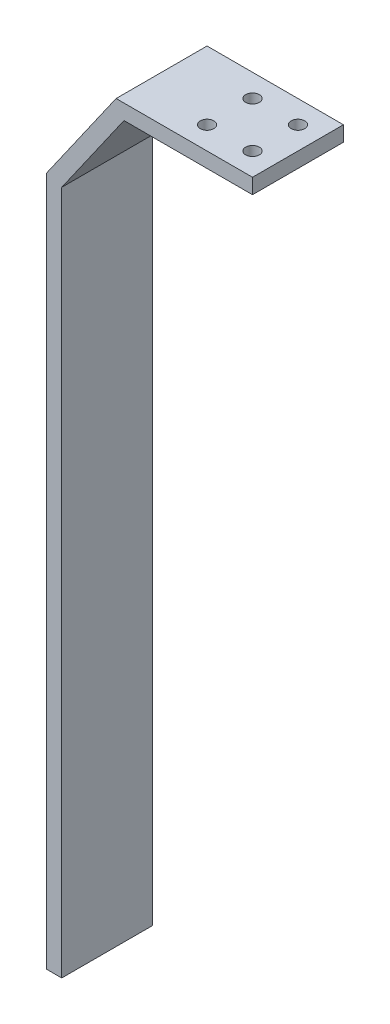
SolidWorks part; units mm, degrees
ref_plane "Front Plane" through (0, 0, 0) normal (0, 0, 1) x (1, 0, 0)
ref_plane "Top Plane" through (0, 0, 0) normal (0, 1, 0) x (1, 0, 0)
ref_plane "Right Plane" through (0, 0, 0) normal (1, 0, 0) x (0, 0, -1)
sketch "Sketch1" plane through (0, 0, 0) normal (0, 0, 1) x (1, 0, 0)
  line L0 (0, 0) -> (0, -445)
  line L1 (0, 0) -> (0, 10)
  line L2 (0, 10) -> (45.8861, 75.5322)
  line L3 (45.8861, 75.5322) -> (135.8861, 75.5322)
  line L4 (10, 0) -> (10, -445)
  line L5 (10, 0) -> (10, 6.847)
  line L6 (10, 6.847) -> (51.0918, 65.5322)
  line L7 (51.0918, 65.5322) -> (135.8861, 65.5322)
  line L8 (135.8861, 75.5322) -> (135.8861, 65.5322)
  line L9 (0, -445) -> (10, -445)
  dimension "D1" = 445
  dimension "D2" = 10
  dimension "D3" = 145
  dimension "D4" = 80
  dimension "D5" = 90
  dimension "D6" = 10
extrude "Boss-Extrude1" add sketch "Sketch1" along normal blind 60
sketch "Sketch2" plane through (0, 75.5322, 0) normal (0, 1, 0) x (1, 0, 0)
  line L3 (135.8861, -60) -> (135.8861, 0) construction
  line L4 (135.8861, 0) -> (45.8861, 0) construction
  circle A3 centre (120.8861, -15) radius 4.5
  circle A4 centre (120.8861, -45) radius 4.5
  circle A5 centre (90.8861, -15) radius 4.5
  circle A6 centre (90.8861, -45) radius 4.5
  dimension "D1" = 15
  dimension "D3" = 9
  dimension "D2" = 15
  dimension "D4" = 30
  dimension "D5" = 15
  dimension "D6" = 30
  dimension "D7" = 0
  dimension "D8" = 30
  dimension "D9" = 30
extrude "Cut-Extrude1" cut sketch "Sketch2" against normal up to next
